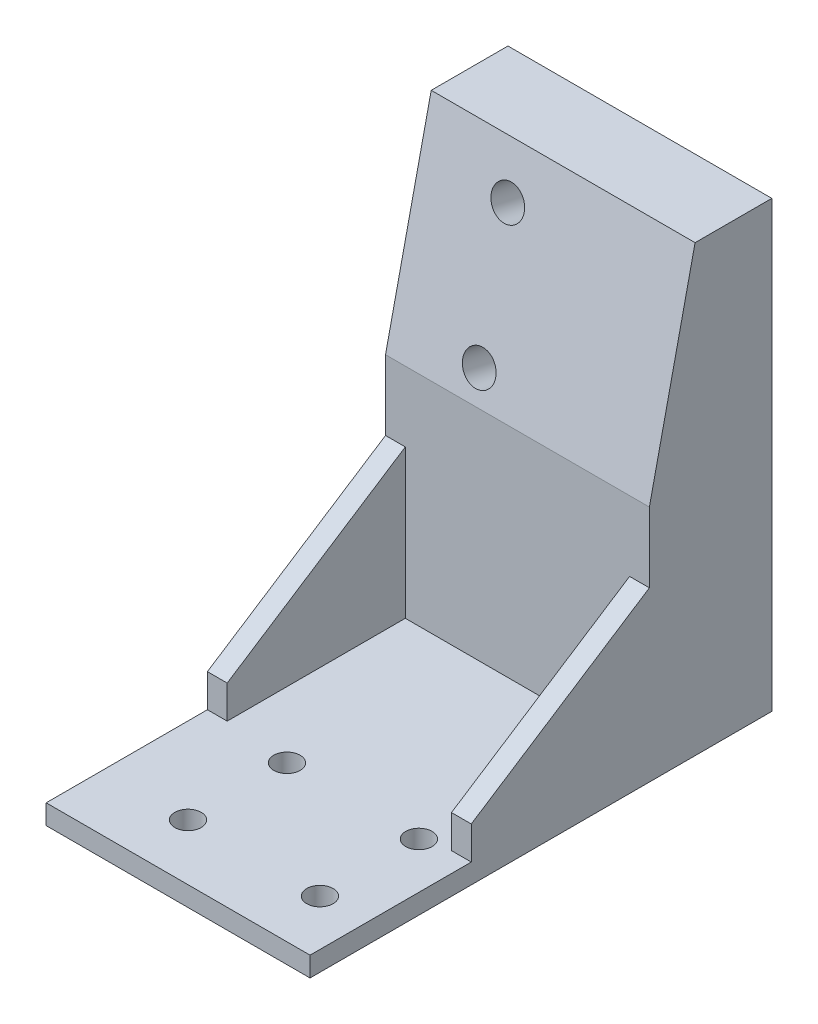
SolidWorks part; units mm, degrees
ref_plane "前视基准面" through (0, 0, 0) normal (0, 0, 1) x (1, 0, 0)
ref_plane "上视基准面" through (0, 0, 0) normal (0, 1, 0) x (1, 0, 0)
ref_plane "右视基准面" through (0, 0, 0) normal (1, 0, 0) x (0, 0, -1)
other "Configuration Table"
sketch "草图1" plane through (0, 0, 0) normal (0, 1, 0) x (1, 0, 0)
  line L1 (-20, -35) -> (20, -35)
  line L2 (-20, -35) -> (-20, 35)
  line L3 (-20, 35) -> (20, 35)
  line L4 (20, -35) -> (20, 35)
  line L5 (-20, -35) -> (20, 35) construction
  line L6 (-20, 35) -> (20, -35) construction
  point P0 (0, 0)
  dimension "D1" = 40
  dimension "D2" = 70
extrude "凸台-拉伸1" add sketch "草图1" along normal blind 3
sketch "草图4" plane through (0, 3, 0) normal (0, 1, 0) x (1, 0, 0)
  line L0 (20, -35) -> (20, 35) construction
  line L1 (-7, -26.5) -> (13, -26.5) construction
  line L2 (-7, -26.5) -> (-7, -11.5) construction
  line L3 (-7, -11.5) -> (13, -11.5) construction
  line L4 (13, -26.5) -> (13, -11.5) construction
  line L5 (-7, -26.5) -> (13, -11.5) construction
  line L6 (-7, -11.5) -> (13, -26.5) construction
  line L7 (-20, -35) -> (20, -35) construction
  circle A0 centre (-7, -11.5) radius 2
  circle A1 centre (13, -11.5) radius 2
  circle A2 centre (-7, -26.5) radius 2
  circle A3 centre (13, -26.5) radius 2
  point P0 (3, -19)
  dimension "D5" = 4
  dimension "D1" = 20
  dimension "D2" = 15
  dimension "D3" = 7
  dimension "D4" = 8.5
extrude "切除-拉伸1" cut sketch "草图4" against normal through all
sketch "草图5" plane through (20, 0, 0) normal (1, 0, 0) x (0, 0, -1)
  line L0 (16.44, 3) -> (16.44, 36.11)
  line L1 (-35, 3) -> (35, 3) construction
  line L2 (16.44, 36.11) -> (23.3661, 67.3515)
  line L3 (23.3661, 67.3515) -> (35, 67.3515)
  line L4 (35, 67.3515) -> (35, 3)
  line L5 (16.44, 3) -> (35, 3)
  dimension "D1" = 18.56
  dimension "D2" = 33.11
  dimension "D3" = 12.5
  dimension "D4" = 32
extrude "凸台-拉伸2" add sketch "草图5" against normal up to surface (40 mm away) up to face at (-20, 1.5, 0)
sketch "草图6" plane through (0, -1.7823, -8.0395) normal (0, 0.2164, 0.9763) x (1, 0, 0)
  line L0 (-6.77, 63.3123) -> (-6.77, 43.3123) construction
  line L1 (-20, 38.8123) -> (-20, 70.8123) construction
  line L2 (-20, 70.8123) -> (20, 70.8123) construction
  circle A0 centre (-6.77, 63.3123) radius 2.5
  circle A1 centre (-6.77, 43.3123) radius 2.5
  dimension "D4" = 5
  dimension "D1" = 13.23
  dimension "D2" = 7.5
  dimension "D3" = 20
extrude "切除-拉伸2" cut sketch "草图6" against normal through all
sketch "草图7" plane through (20, 0, 0) normal (1, 0, 0) x (0, 0, -1)
  line L0 (16.44, 25.5) -> (-10.56, 8)
  line L1 (16.44, 36.11) -> (16.44, 3) construction
  line L2 (-10.56, 8) -> (-10.56, 3)
  line L3 (-35, 3) -> (16.44, 3) construction
  line L4 (-10.56, 3) -> (16.44, 3)
  line L5 (16.44, 3) -> (16.44, 25.5)
  dimension "D1" = 22.5
  dimension "D2" = 27
  dimension "D3" = 5
extrude "凸台-拉伸3" add sketch "草图7" against normal blind 3
mirror "镜向1" about plane through (0, 0, 0) normal (1, 0, 0) of "凸台-拉伸3"
